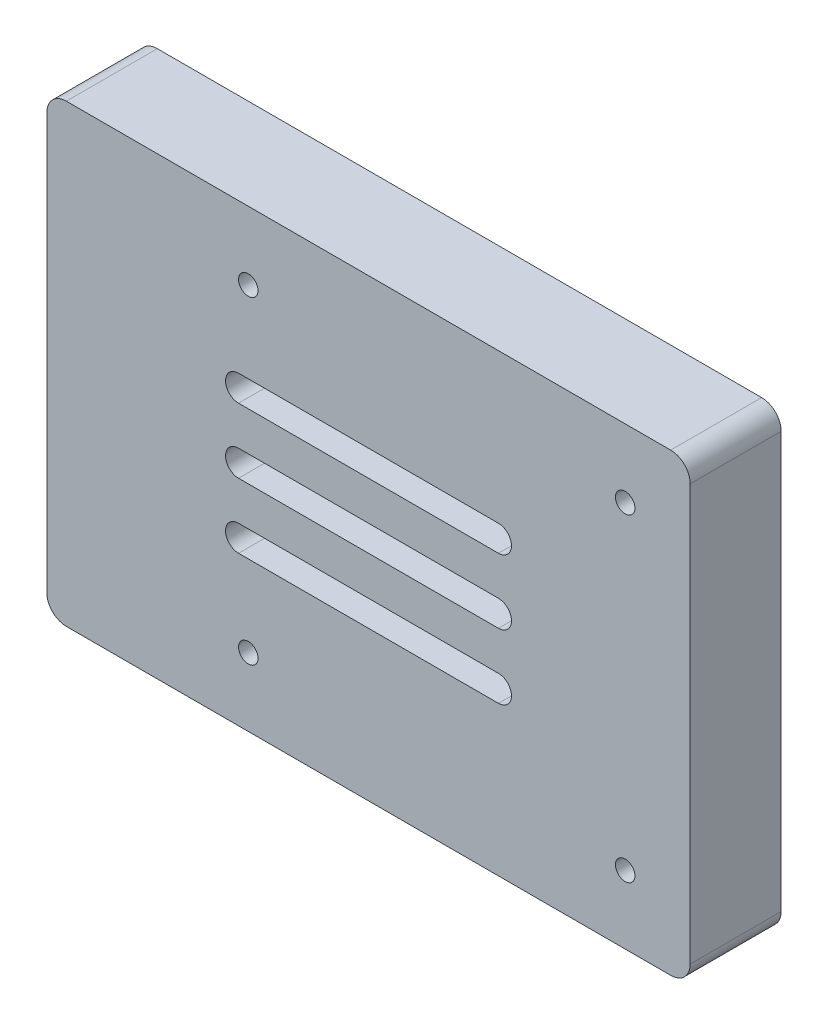
SolidWorks part; units mm, degrees
ref_plane "Plan de face" through (0, 0, 0) normal (0, 0, 1) x (1, 0, 0)
ref_plane "Plan de dessus" through (0, 0, 0) normal (0, 1, 0) x (1, 0, 0)
ref_plane "Plan de droite" through (0, 0, 0) normal (1, 0, 0) x (0, 0, -1)
sketch "Esquisse1" plane through (0, 0, 0) normal (0, 0, 1) x (1, 0, 0)
  line L1 (-46.5, -35) -> (46.5, -35)
  line L2 (-49.5, -32) -> (-49.5, 32)
  line L3 (-46.5, 35) -> (46.5, 35)
  line L4 (49.5, -32) -> (49.5, 32)
  line L5 (-49.5, -35) -> (49.5, 35) construction
  line L6 (-49.5, 35) -> (49.5, -35) construction
  line L7 (-44.5, -33) -> (44.5, -33)
  line L8 (-47.5, -30) -> (-47.5, 30)
  line L9 (-44.5, 33) -> (44.5, 33)
  line L10 (47.5, -30) -> (47.5, 30)
  line L11 (-47.5, -33) -> (47.5, 33) construction
  line L12 (-47.5, 33) -> (47.5, -33) construction
  line L13 (-51.0384, 0) -> (57.3436, 0) construction
  arc A0 (-49.5, 32) -> (-46.5, 35) centre (-46.5, 32) cw
  arc A1 (-46.5, -35) -> (-49.5, -32) centre (-46.5, -32) cw
  arc A2 (46.5, 35) -> (49.5, 32) centre (46.5, 32) cw
  arc A3 (46.5, -35) -> (49.5, -32) centre (46.5, -32) ccw
  arc A4 (-47.5, 30) -> (-44.5, 33) centre (-44.5, 30) cw
  arc A5 (44.5, 33) -> (47.5, 30) centre (44.5, 30) cw
  arc A6 (-44.5, -33) -> (-47.5, -30) centre (-44.5, -30) cw
  arc A7 (44.5, -33) -> (47.5, -30) centre (44.5, -30) ccw
  point P0 (0, 0)
  point P18 (0, 0)
  dimension "D3" = 3
  dimension "D4" = 3
  dimension "D5" = 3
  dimension "D6" = 3
  dimension "D9" = 3
  dimension "D10" = 3
  dimension "D11" = 3
  dimension "D12" = 3
  dimension "D1" = 70
  dimension "D2" = 99
  dimension "D7" = 66
  dimension "D8" = 95
extrude "Boss.-Extru.1" add sketch "Esquisse1" along normal blind 10 contours L1 A3 L4 A2 L3 A0 L2 A1 A7 L7 A6 L8 A4 L9 A5 L10
sketch "Esquisse2" plane through (0, 0, 0) normal (0, 0, 1) x (1, 0, 0)
  line L4 (-46.5, -35) -> (46.5, -35)
  line L5 (-49.5, -32) -> (-49.5, 32)
  line L6 (-46.5, 35) -> (46.5, 35)
  line L7 (49.5, -32) -> (49.5, 32)
  line L8 (-49.5, -35) -> (49.5, 35) construction
  line L9 (-49.5, 35) -> (49.5, -35) construction
  arc A4 (-49.5, 32) -> (-46.5, 35) centre (-46.5, 32) cw
  arc A5 (-46.5, -35) -> (-49.5, -32) centre (-46.5, -32) cw
  arc A6 (46.5, 35) -> (49.5, 32) centre (46.5, 32) cw
  arc A7 (46.5, -35) -> (49.5, -32) centre (46.5, -32) ccw
  point P11 (0, 0)
  dimension "D9" = 3
  dimension "D10" = 3
  dimension "D11" = 3
  dimension "D12" = 3
  dimension "D7" = 99
  dimension "D8" = 70
extrude "Boss.-Extru.2" add sketch "Esquisse2" along normal blind 4 from surface at 10 starting at face at (0, 0, 10)
sketch "Esquisse3" plane through (0, 0, 14) normal (0, 0, 1) x (1, 0, 0)
  line L0 (49.0956, 0) -> (-50.8416, 0) construction
  line L4 (47.5, -30) -> (47.5, 30) construction
  circle A0 centre (39.5, 24.5) radius 1.5
  circle A1 centre (-18.5, 24.5) radius 1.5
  circle A4 centre (39.5, -24.5) radius 1.5
  circle A5 centre (-18.5, -24.5) radius 1.5
  dimension "D3" = 3
  dimension "D5" = 3
  dimension "D1" = 24.5
  dimension "D2" = 24.5
  dimension "D4" = 58
  dimension "D6" = 8
extrude "Enlèv. mat.-Extru.1" cut sketch "Esquisse3" against normal through all
sketch "Esquisse4" plane through (0, 0, 14) normal (0, 0, 1) x (1, 0, 0)
  line L0 (20, 0) -> (-20, 0) construction
  line L1 (20, -2) -> (-20, -2)
  line L2 (20, 2) -> (-20, 2)
  line L3 (20, -10) -> (-20, -10) construction
  line L4 (20, -12) -> (-20, -12)
  line L5 (20, -8) -> (-20, -8)
  line L6 (20, 10) -> (-20, 10) construction
  line L7 (20, 8) -> (-20, 8)
  line L8 (20, 12) -> (-20, 12)
  arc A0 (20, -2) -> (20, 2) centre (20, 0) ccw
  arc A1 (-20, 2) -> (-20, -2) centre (-20, 0) ccw
  arc A2 (20, -12) -> (20, -8) centre (20, -10) ccw
  arc A3 (-20, -8) -> (-20, -12) centre (-20, -10) ccw
  arc A4 (20, 8) -> (20, 12) centre (20, 10) ccw
  arc A5 (-20, 12) -> (-20, 8) centre (-20, 10) ccw
  point P3 (0, 0)
  point P13 (0, -10)
  point P19 (0, 10)
  dimension "D2" = 2
  dimension "D1" = 40
  dimension "D3" = 2
  dimension "D5" = 10
  dimension "D6" = 10
  dimension "D4" = 2
extrude "Enlèv. mat.-Extru.2" cut sketch "Esquisse4" against normal blind 5
